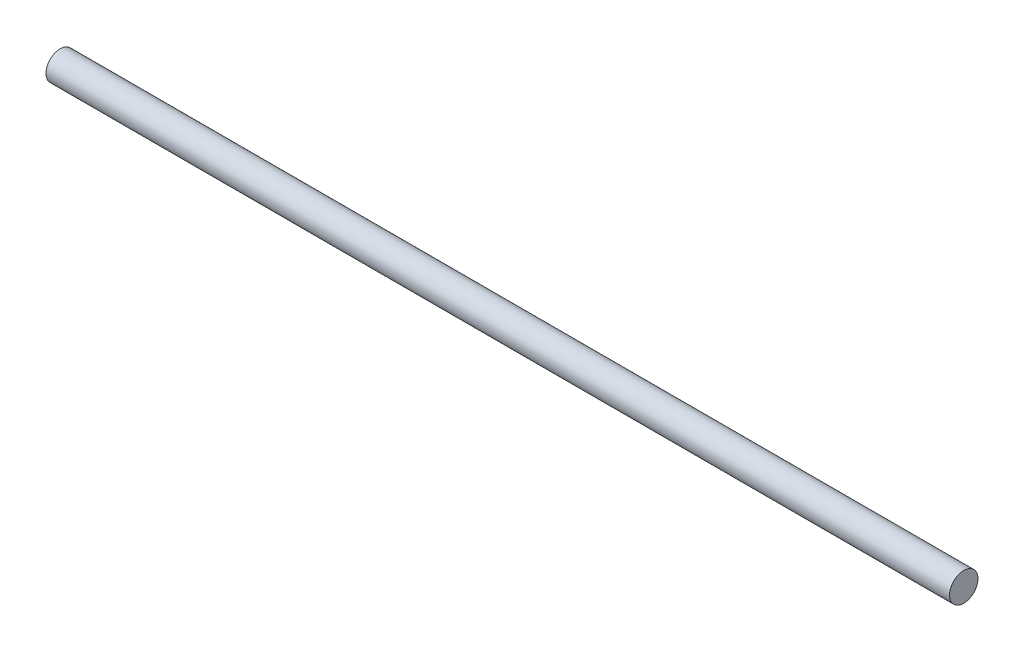
SolidWorks part; units mm, degrees
ref_plane "Front Plane" through (0, 0, 0) normal (0, 0, 1) x (1, 0, 0)
ref_plane "Top Plane" through (0, 0, 0) normal (0, 1, 0) x (1, 0, 0)
ref_plane "Right Plane" through (0, 0, 0) normal (1, 0, 0) x (0, 0, -1)
sketch "Sketch1" plane through (0, 0, 0) normal (1, 0, 0) x (0, 0, -1)
  circle A0 centre (0, 0) radius 4.0005
  dimension "D1" = 8.001
extrude "Boss-Extrude1" add sketch "Sketch1" along normal blind 254
